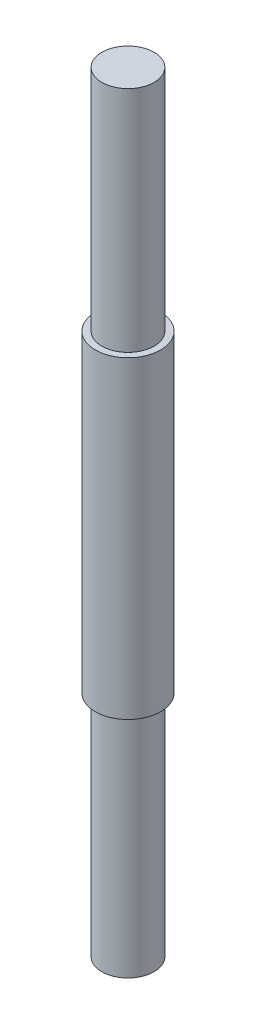
SolidWorks part; units mm, degrees
ref_plane "前视基准面" through (0, 0, 0) normal (0, 0, 1) x (1, 0, 0)
ref_plane "上视基准面" through (0, 0, 0) normal (0, 1, 0) x (1, 0, 0)
ref_plane "右视基准面" through (0, 0, 0) normal (1, 0, 0) x (0, 0, -1)
sketch "草图1" plane through (0, 0, 0) normal (0, 1, 0) x (1, 0, 0)
  circle A0 centre (0, 0) radius 5
  dimension "D1" = 10
extrude "凸台-拉伸1" add sketch "草图1" along normal blind 48
sketch "草图3" plane through (0, 0, 0) normal (0, -1, 0) x (1, 0, 0)
  circle A0 centre (0, 0) radius 4
  dimension "D1" = 8
extrude "凸台-拉伸2" add sketch "草图3" along normal blind 35
sketch "草图4" plane through (0, 48, 0) normal (0, 1, 0) x (1, 0, 0)
  circle A0 centre (0, 0) radius 4
  dimension "D1" = 8
extrude "凸台-拉伸3" add sketch "草图4" along normal blind 35
